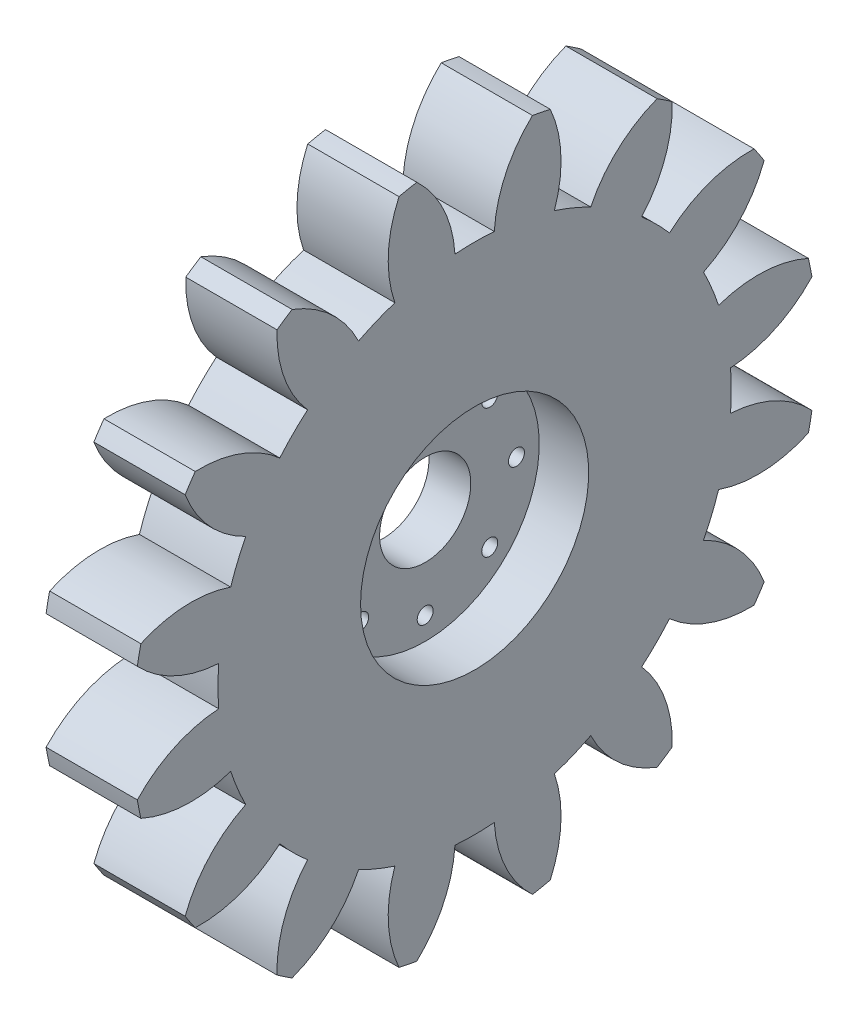
SolidWorks part; units mm, degrees
ref_plane "Plane1" through (0, 0, 0) normal (0, 0, 1) x (1, 0, 0)
ref_plane "Plane2" through (0, 0, 0) normal (0, 1, 0) x (1, 0, 0)
ref_plane "Plane3" through (0, 0, 0) normal (1, 0, 0) x (0, 0, -1)
sketch "HoldingSke" plane through (0, 0, 0) normal (0, 1, 0) x (1, 0, 0)
  line L0 (0, 0) -> (0.1923, -0.0551)
  line L1 (-15, 0) -> (100, 0) construction
  line L2 (0, 0) -> (-2.1039, 2.3779)
  line L3 (0, 0) -> (-11.863, 4.5341)
  line L4 (0, 0) -> (8.3015, 2.3804)
  line L5 (0, 0) -> (-46.8476, -17.4728)
  line L6 (0, 0) -> (-9.9476, -6.7116)
  line L7 (-2.1039, 2.3779) -> (8.6586, 51.2059)
  line L8 (-76.2, 54.61) -> (-73.9, 54.61)
  line L9 (-71.009, 38.7566) -> (-53.1078, 45.2721)
  line L10 (-76.2, 71.12) -> (104.1128, 71.12)
  line L11 (0, 0) -> (-12, 0)
  line L12 (-76.2, 101.6) -> (-76.033, 101.6)
  line L13 (24.9733, 27.94) -> (52.9518, 28.4284)
  line L14 (24.9733, 27.94) -> (24.9743, 27.94)
  line L15 (24.9733, 27.94) -> (100.4006, 29.5858)
  line L16 (-63.627, -5) -> (-12.827, -5)
  circle A0 centre (0, 0) radius 6
  circle A1 centre (0, 0) radius 33.749
  circle A2 centre (0, 0) radius 37.5
  circle A3 centre (0, 0) radius 6
  dimension "MHD" = 67.498
  dimension "Hub_dia" = 75
  dimension "Bore" = 12
  dimension "MBD" = 12
  dimension "Num_teeth" = 16
  dimension "Pitch" = 0.2
  dimension "Overall_len" = 50
  dimension "Show_teeth" = 16
  dimension "Thickness" = 12
  dimension "OAL" = 50.0001
  dimension "T_dim" = 2.3
  dimension "Ap" = 20
  dimension "H" = 19.05
  dimension "Pitch_radius" = 180.3128
  dimension "Width" = 12
  dimension "Backlash" = 0.167
  dimension "Addendum_fac" = 1
  dimension "Dedendum_fac" = 1.25
  dimension "Clearance_fac" = 0.25
  dimension "Dedendum_add" = 0.001
  dimension "Module" = 5
sketch "BasProSke" plane through (0, 0, 0) normal (0, 1, 0) x (1, 0, 0)
  line L0 (-10, 0) -> (4, 0) construction
  line L1 (0, 0) -> (0, 45)
  line L2 (0, 0) -> (4, 0)
  line L3 (12, 15) -> (12, 45)
  line L4 (12, 45) -> (0, 45)
  line L5 (4, 0) -> (4, 6)
  line L6 (4, 6) -> (5.5, 6)
  line L7 (5.5, 6) -> (5.5, 15)
  line L8 (5.5, 15) -> (12, 15)
  line L9 (12, 0) -> (60, 0) construction
  dimension "Thickness" = 12
  dimension "Diameter" = 90
  dimension "D1" = 15
  dimension "D2" = 1.5
  dimension "D3" = 6
  dimension "D4" = 6.5
  dimension "D5" = 12
revolve "Base-Revolve" add sketch "BasProSke" angle 360 about L0
sketch "TooCutSke" plane through (0, 0, 0) normal (1, 0, 0) x (0, 0, -1)
  line L1 (0, 0) -> (0, 107) construction
  line L2 (0, 0) -> (-4.2127, 39.7775) construction
  line L3 (0, 0) -> (-15.5429, 78.1393) construction
  line L4 (-4.2127, 39.7775) -> (-7.7714, 39.0697) construction
  arc A0 (2.5852, 33.6498) -> (-2.5852, 33.6498) centre (0, 0) ccw
  arc A1 (7.6282, 44.3745) -> (-7.6282, 44.3745) centre (0, 0) ccw
  circle A2 centre (0, 0) radius 40 construction
  circle A3 centre (0, 0) radius 37.5877 construction
  arc A4 (-2.5852, 33.6498) -> (-7.6282, 44.3745) centre (-18.5563, 32.6879) ccw
  arc A5 (7.6282, 44.3745) -> (2.5852, 33.6498) centre (18.5563, 32.6879) ccw
  dimension "Root_dia" = 67.498
  dimension "Overcut_dia" = 90.0508
  dimension "Pitch_dia" = 80
  dimension "Base_dia" = 75.1754
  dimension "Flank_rad" = 16
  dimension "Half_ang" = 11.25
  dimension "Half_CT" = 3.6284
extrude "ToothCut" cut sketch "TooCutSke" along normal through all
fillet "Breaks" [suppressed] radius 0.1
fillet "RootFillets" [suppressed] radius 1.251
pattern_circular "TeethCuts" count 16 every 22.5 about axis through (-10, 0, 0) along (1, 0, 0) of "ToothCut", "RootFillets", "Breaks"
sketch "HubNeaOneSke" plane through (0, 0, 0) normal (-1, 0, 0) x (0, 0, 1)
  circle A0 centre (0, 0) radius 33.749
  dimension "Diameter" = 67.498
extrude "HubNearOne" [suppressed] add sketch "HubNeaOneSke" along normal blind 38.0001
sketch "HubNeaBotSke" plane through (0, 0, 0) normal (-1, 0, 0) x (0, 0, 1)
  circle A0 centre (0, 0) radius 33.749
  dimension "Diameter" = 67.498
extrude "HubNearBoth" [suppressed] add sketch "HubNeaBotSke" along normal blind 19
ref_plane "FarPln" through (12, 0, 0) normal (1, 0, 0) x (0, 0, -1)
sketch "HubFarSke" plane through (12, 0, 0) normal (1, 0, 0) x (0, 0, -1)
  circle A0 centre (0, 0) radius 33.749
  dimension "Diameter" = 67.498
extrude "HubFar" [suppressed] add sketch "HubFarSke" along normal blind 19
sketch "BorSke" plane through (0, 0, 0) normal (1, 0, 0) x (0, 0, -1)
  circle A0 centre (0, 0) radius 6
  dimension "Diameter" = 12
extrude "Bore" cut sketch "BorSke" along normal mid plane 100.0001
sketch "KeySke" plane through (0, 0, 0) normal (1, 0, 0) x (0, 0, -1)
  line L0 (-2.5, 0) -> (-2.5, 8.3)
  line L1 (-2.5, 8.3) -> (2.5, 8.3)
  line L2 (2.5, 8.3) -> (2.5, 0)
  line L3 (0, 0) -> (0, 34) construction
  line L4 (-2.5, 0) -> (2.5, 0)
  dimension "Offset" = 8.3
  dimension "Width" = 5
extrude "Keyway" [suppressed] cut sketch "KeySke" along normal mid plane 100.0001
pattern_circular "Keyway2" [suppressed] count 2 every 90 about axis through (-10, 0, 0) along (1, 0, 0)
sketch "Sketch1" plane through (12, 0, 0) normal (1, 0, 0) x (0, 0, -1)
  circle A0 centre (0, 12) radius 1.05
  circle A4 centre (8.4853, 8.4853) radius 1.05
  circle A5 centre (12, 0) radius 1.05
  circle A6 centre (8.4853, -8.4853) radius 1.05
  circle A7 centre (0, -12) radius 1.05
  circle A8 centre (-8.4853, -8.4853) radius 1.05
  circle A9 centre (-12, 0) radius 1.05
  circle A10 centre (-8.4853, 8.4853) radius 1.05
  point P11 (0, 0)
  point P22 (0, 0)
  dimension "D1" = 2.1
  dimension "D3" = 12
  dimension "D4" = 33.6498
  dimension "D5" = 10.7029
  dimension "D6" = 7.6049
  dimension "D7" = 10.1901
  dimension "D2" = 8
extrude "Cut-Extrude1" cut sketch "Sketch1" against normal blind 120
equation "' \"Module@HoldingSke\" = 6.35"
equation "' \"Num_teeth@HoldingSke\" = 12"
equation "' \"Ap@HoldingSke\" =  20"
equation "' \"Ap@HoldingSke\" = 20"
equation "' \"Width@HoldingSke\" = 0.5 * 25.4"
equation "' \"Hub_dia@HoldingSke\"= 1 * 25.4"
equation "' \"Hub_dia@HoldingSke\" = 1 * 25.4"
equation "' \"Overall_len@HoldingSke\" = 1.0 * 25.4"
equation "' \"Bore@HoldingSke\" = 0.75 * 25.4"
equation "' \"T_dim@HoldingSke\" = 0.1 * 25.4"
equation "' \"Width@KeySke\" = 0.25 * 25.4"
equation "' \"Show_teeth@HoldingSke\" = 13"
equation "' \"Backlash@HoldingSke\" = 0.009 * 25.4"
equation "' \"Addendum_fac@HoldingSke\" = 1.0"
equation "' \"Dedendum_fac@HoldingSke\" = 1.25"
equation "' \"Dedendum_add@HoldingSke\" = 0.00005 * 25.4"
equation "' \"Clearance_fac@HoldingSke\" = 0.25"
equation "\"Pitch@HoldingSke\" = 1 / \"Module@HoldingSke\""
equation "\"Overcut_dia@TooCutSke\" = (\"Num_teeth@HoldingSke\" + 2 * \"Addendum_fac@HoldingSke\") / \"Pitch@HoldingSke\" + 0.002 * 25.4"
equation "\"Pitch_dia@TooCutSke\" = \"Num_teeth@HoldingSke\" / \"Pitch@HoldingSke\""
equation "\"Base_dia@TooCutSke\" = \"Num_teeth@HoldingSke\" / \"Pitch@HoldingSke\" * cos((\"Ap@HoldingSke\"  * 3.14159265 / 180))"
equation "\"Root_dia@TooCutSke\" = (\"Num_teeth@HoldingSke\" + 2) / \"Pitch@HoldingSke\" - 2 * (\"Addendum_fac@HoldingSke\" + \"Dedendum_fac@HoldingSke\") / \"Pitch@HoldingSke\" - \"Dedendum_add@HoldingSke\" * 2"
equation "\"Half_ang@TooCutSke\" = 180 / \"Num_teeth@HoldingSke\""
equation "\"Half_CT@TooCutSke\" = \"Num_teeth@HoldingSke\" / \"Pitch@HoldingSke\" * sin((3.14159265 / 2 / \"Num_teeth@HoldingSke\")) / 2 - 7 * \"Backlash@HoldingSke\" / 4"
equation "\"Flank_rad@TooCutSke\" = \"Num_teeth@HoldingSke\" / \"Pitch@HoldingSke\" / 5"
equation "\"Radius@RootFillets\" = \"Clearance_fac@HoldingSke\" / \"Pitch@HoldingSke\" + \"Dedendum_add@HoldingSke\""
equation "\"Break_rad@Breaks\" = 0.02 / \"Pitch@HoldingSke\""
equation "\"Thickness@HoldingSke\" = \"Width@HoldingSke\""
equation "\"OAL@HoldingSke\" = \"Thickness@HoldingSke\""
equation "\"MHD@HoldingSke\" = (\"Num_teeth@HoldingSke\" + 2) / \"Pitch@HoldingSke\" - 2 * (\"Addendum_fac@HoldingSke\" + \"Dedendum_fac@HoldingSke\")  / \"Pitch@HoldingSke\" - \"Dedendum_add@HoldingSke\" * 2"
equation "\"MBD@HoldingSke\" = (\"Num_teeth@HoldingSke\" + 2) / \"Pitch@HoldingSke\" - 2 * (\"Addendum_fac@HoldingSke\" + \"Dedendum_fac@HoldingSke\")  / \"Pitch@HoldingSke\" - \"Dedendum_add@HoldingSke\" * 2 - 0.002 * 25.4"
equation "\"MHD@HoldingSke\" = ((sgn( \"MHD@HoldingSke\" - \"Hub_dia@HoldingSke\" )-1)*( \"MHD@HoldingSke\" - \"Hub_dia@HoldingSke\" ))/-2+ \"Hub_dia@HoldingSke\""
equation "\"MBD@HoldingSke\" = ((sgn( \"MBD@HoldingSke\" - \"Bore@HoldingSke\" )-1)*( \"MBD@HoldingSke\" - \"Bore@HoldingSke\" ))/-2+ \"Bore@HoldingSke\""
equation "\"OAL@HoldingSke\" = ((sgn( \"OAL@HoldingSke\" - \"Overall_len@HoldingSke\" )+1)*( \"OAL@HoldingSke\" - \"Overall_len@HoldingSke\" ))/2 + \"Overall_len@HoldingSke\" + 0.000002 * 25.4"
equation "\"Num_teeth@TeethCuts\" = int( \"Show_teeth@HoldingSke\" ) + 1"
equation "\"Num_teeth@TeethCuts\" = ((sgn( \"Num_teeth@TeethCuts\" - \"Num_teeth@HoldingSke\" )-1)*( \"Num_teeth@TeethCuts\" - \"Num_teeth@HoldingSke\" ))/-2+ \"Num_teeth@HoldingSke\""
equation "\"Num_teeth@TeethCuts\" = ((sgn( \"Num_teeth@TeethCuts\" - 2.0)+1)*( \"Num_teeth@TeethCuts\" - 2.0))/2 +2.0"
equation "\"Angle@TeethCuts\" = 360.0 / \"Num_teeth@HoldingSke\""
equation "\"Diameter@BasProSke\" = (\"Num_teeth@HoldingSke\" + 2 * \"Addendum_fac@HoldingSke\") / \"Pitch@HoldingSke\""
equation "\"Thickness@BasProSke\"  = \"Thickness@HoldingSke\""
equation "' \"Fillet_rad@BasProSke\" =  \"Thickness@HoldingSke\" * 0.05"
equation "' \"Fillet_rad@BasProSke\" = \"Thickness@HoldingSke\" * 0.05"
equation "\"MHD@HoldingSke\" = ((sgn( \"MHD@HoldingSke\" - \"Root_dia@TooCutSke\" )-1)*( \"MHD@HoldingSke\" - \"Root_dia@TooCutSke\" ))/-2+ \"Root_dia@TooCutSke\""
equation "\"Diameter@HubNeaOneSke\" = \"MHD@HoldingSke\""
equation "\"Length@HubNearOne\" = \"OAL@HoldingSke\" - \"Thickness@BasProSke\""
equation "\"Diameter@HubNeaBotSke\" = \"MHD@HoldingSke\""
equation "\"Length@HubNearBoth\" = ( \"OAL@HoldingSke\" - \"Thickness@BasProSke\" ) / 2.0"
equation "\"Thickness@FarPln\" = \"Thickness@BasProSke\""
equation "\"Diameter@HubFarSke\" = \"MHD@HoldingSke\""
equation "\"Length@HubFar\" = ( \"OAL@HoldingSke\" - \"Thickness@BasProSke\" ) / 2.0"
equation "\"Diameter@BorSke\" = \"MBD@HoldingSke\""
equation "\"D1@Bore\" = \"OAL@HoldingSke\" * 2.0"
equation "\"D1@Keyway\" = \"OAL@HoldingSke\" * 2.0"
equation "\"Offset@KeySke\" = \"T_dim@HoldingSke\" + \"MBD@HoldingSke\" / 2.0"
